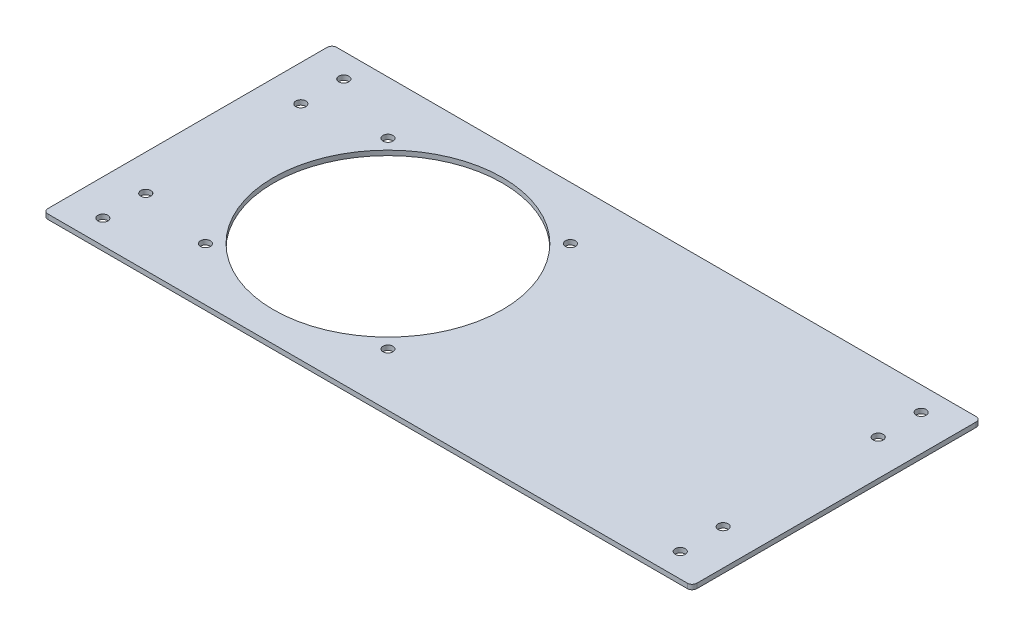
SolidWorks part; units mm, degrees
ref_plane "前视基准面" through (0, 0, 0) normal (0, 0, 1) x (1, 0, 0)
ref_plane "上视基准面" through (0, 0, 0) normal (0, 1, 0) x (1, 0, 0)
ref_plane "右视基准面" through (0, 0, 0) normal (1, 0, 0) x (0, 0, -1)
other "Configuration Table"
sketch "草图1" plane through (0, 0, 0) normal (0, 1, 0) x (1, 0, 0)
  line L0 (-144.8736, 0) -> (184.4135, 0) construction
  line L1 (0, 106.6197) -> (0, -106.6197) construction
  line L3 (-136, -60.5) -> (136, -60.5)
  line L4 (-136, -60.5) -> (-136, 60.5)
  line L5 (-136, 60.5) -> (136, 60.5)
  line L6 (136, -60.5) -> (136, 60.5)
  line L7 (-136, -60.5) -> (136, 60.5) construction
  line L8 (-136, 60.5) -> (136, -60.5) construction
  point P5 (0, 0)
  dimension "D1" = 121
  dimension "D2" = 272
extrude "凸台-拉伸1" add sketch "草图1" along normal blind 2
sketch "草图2" plane through (0, 2, 0) normal (0, 1, 0) x (1, 0, 0)
  line L0 (-202.9721, 0) -> (179.541, 0) construction
  line L1 (0, 104.2685) -> (0, -113.6409) construction
  line L2 (121, 96.6534) -> (121, -100.168) construction
  line L3 (136, -60.5) -> (136, 60.5) construction
  line L4 (136, 60.5) -> (-136, 60.5) construction
  circle A0 centre (121, 50.5) radius 2.1
  circle A1 centre (121, 32.5) radius 2.1
  circle A2 centre (121, -32.5) radius 2.1
  circle A3 centre (121, -50.5) radius 2.1
  circle A4 centre (-121, -50.5) radius 2.1
  circle A5 centre (-121, -32.5) radius 2.1
  circle A6 centre (-121, 32.5) radius 2.1
  circle A7 centre (-121, 50.5) radius 2.1
  dimension "D4" = 4.2
  dimension "D5" = 4.2
  dimension "D1" = 15
  dimension "D2" = 18
  dimension "D3" = 10
extrude "切除-拉伸1" cut sketch "草图2" against normal through all
fillet "圆角1" radius 2 4 edges at (136, 1, -60.5) (136, 1, 60.5) (-136, 1, -60.5) (-136, 1, 60.5)
sketch "草图3" plane through (0, 0, 0) normal (0, -1, 0) x (1, 0, 0)
  line L0 (-152.6091, 0) -> (167.5499, 0) construction
  line L2 (-90.25, -38.25) -> (-13.75, -38.25) construction
  line L3 (-90.25, -38.25) -> (-90.25, 38.25) construction
  line L4 (-90.25, 38.25) -> (-13.75, 38.25) construction
  line L5 (-13.75, -38.25) -> (-13.75, 38.25) construction
  line L6 (-90.25, -38.25) -> (-13.75, 38.25) construction
  line L7 (-90.25, 38.25) -> (-13.75, -38.25) construction
  circle A0 centre (-13.75, -38.25) radius 2.1
  circle A1 centre (-13.75, 38.25) radius 2.06
  circle A2 centre (-90.25, 38.25) radius 2.1
  circle A3 centre (-90.25, -38.25) radius 2.1
  circle A4 centre (-52, 0) radius 48
  point P3 (-52, 0)
  dimension "D4" = 4.2
  dimension "D5" = 4.12
  dimension "D6" = 4.2
  dimension "D7" = 4.2
  dimension "D8" = 96
  dimension "D1" = 76.5
  dimension "D2" = 76.5
  dimension "D3" = 52
extrude "切除-拉伸2" cut sketch "草图3" against normal through all
